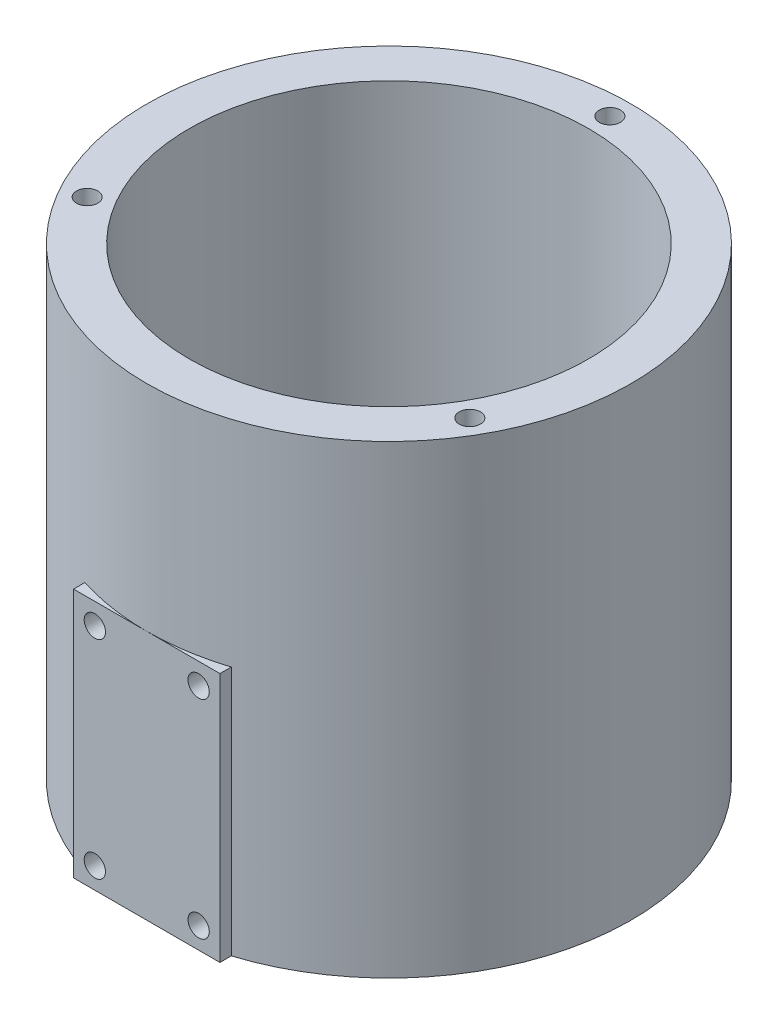
SolidWorks part; units mm, degrees
ref_plane "Front Plane" through (0, 0, 0) normal (0, 0, 1) x (1, 0, 0)
ref_plane "Top Plane" through (0, 0, 0) normal (0, 1, 0) x (1, 0, 0)
ref_plane "Right Plane" through (0, 0, 0) normal (1, 0, 0) x (0, 0, -1)
sketch "Sketch1" plane through (0, 0, 0) normal (0, 1, 0) x (1, 0, 0)
  circle A0 centre (0, 0) radius 45.5
  circle A2 centre (0, 0) radius 33.5
  dimension "D1" = 91
  dimension "D3" = 67
extrude "Boss-Extrude1" add sketch "Sketch1" along normal blind 4
sketch "Sketch2" plane through (0, 4, 0) normal (0, 1, 0) x (1, 0, 0)
  circle A0 centre (0, 0) radius 37.5
  circle A1 centre (0, 0) radius 45.5
  dimension "D1" = 91
  dimension "D2" = 75
extrude "Boss-Extrude2" add sketch "Sketch2" along normal blind 83.3
sketch "Sketch4" plane through (0, 87.3, 0) normal (0, 1, 0) x (1, 0, 0)
  line L0 (0, 0) -> (0, 41.5) construction
  circle A0 centre (0, 41.5) radius 2
  dimension "D1" = 41.5
  dimension "D2" = 4
extrude "Cut-Extrude1" cut sketch "Sketch4" against normal blind 6 contours A0
pattern_circular "CirPattern1" count 3 over 360 about axis through (0, 0, 0) along (0, 1, 0) of "Cut-Extrude1"
sketch "Sketch6" plane through (0, 87.3, 0) normal (0, 1, 0) x (1, 0, 0)
  line L0 (0, 0) -> (0, -45.5)
  circle A0 centre (0, 0) radius 45.5 construction
ref_plane "Plane1" through (0, 87.3, 45.5) normal (0, 0, 1) x (1, 0, 0)
sketch "Sketch7" plane through (0, 87.3, 45.5) normal (0, 0, 1) x (1, 0, 0)
  line L0 (-13.75, -87.3) -> (13.75, -87.3)
  line L1 (13.75, -87.3) -> (13.75, -40.3)
  line L2 (13.75, -40.3) -> (-13.75, -40.3)
  line L3 (-13.75, -40.3) -> (-13.75, -87.3)
  line L4 (-45.5, -87.3) -> (45.5, -87.3) construction
  line L8 (45.5, -87.3) -> (45.5, 0) construction
  dimension "D1" = 27.5
  dimension "D2" = 47
  dimension "D3" = 0
  dimension "D4" = 31.75
extrude "Boss-Extrude4" add sketch "Sketch7" against normal up to next
sketch "Sketch9" plane through (0, 0, 45.5) normal (0, 0, 1) x (1, 0, 0)
  line L0 (-13.75, 0) -> (13.75, 0) construction
  line L1 (-13.75, 47) -> (-13.75, 0) construction
  line L2 (13.75, 0) -> (13.75, 47) construction
  circle A0 centre (-9.75, 4) radius 2
  circle A1 centre (9.75, 4) radius 2
  point P8 (0, 0)
  point P10 (8.3929, 3.3276)
  dimension "D1" = 4
  dimension "D4" = 4
  dimension "D2" = 4
  dimension "D3" = 4
  dimension "D5" = 4
extrude "Cut-Extrude2" cut sketch "Sketch9" against normal blind 6
sketch "Sketch10" plane through (0, 0, 45.5) normal (0, 0, 1) x (1, 0, 0)
  line L0 (-13.75, 8) -> (13.75, 8)
  line L1 (-13.75, 47) -> (-13.75, 0) construction
  line L2 (13.75, 0) -> (13.75, 47) construction
  line L3 (-13.75, 0) -> (13.75, 0) construction
  line L4 (-13.75, 39) -> (13.75, 39)
  line L5 (-13.75, 47) -> (-13.75, 0) construction
  circle A0 centre (-9.75, 43) radius 2
  circle A1 centre (9.75, 43) radius 2
  dimension "D3" = 4
  dimension "D1" = 8
  dimension "D2" = 31
  dimension "D4" = 4
  dimension "D5" = 4
  dimension "D6" = 4
extrude "Cut-Extrude3" cut sketch "Sketch10" against normal blind 6 contours A0 | A1
